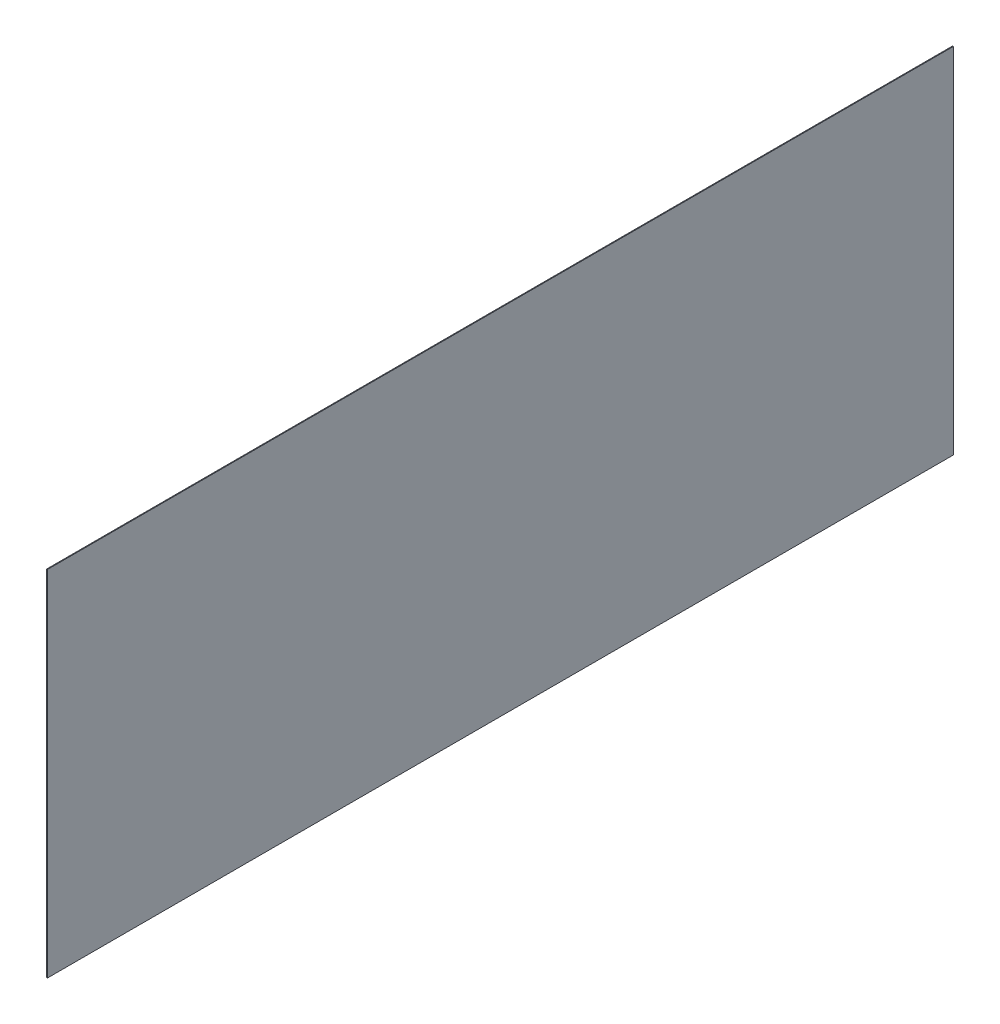
SolidWorks part; units mm, degrees
material "POLYURETHANE (11671)"
ref_plane "Front" through (0, 0, 0) normal (0, 0, 1) x (1, 0, 0)
ref_plane "Top" through (0, 0, 0) normal (0, 1, 0) x (1, 0, 0)
ref_plane "Right" through (0, 0, 0) normal (1, 0, 0) x (0, 0, -1)
sketch "Sketch1" plane through (0, 0, 0) normal (1, 0, 0) x (0, 0, -1)
  line L1 (-2876, 1123.5) -> (2876, 1123.5)
  line L2 (-2876, 1123.5) -> (-2876, -1123.5)
  line L3 (-2876, -1123.5) -> (2876, -1123.5)
  line L4 (2876, 1123.5) -> (2876, -1123.5)
  line L5 (-2876, 1123.5) -> (2876, -1123.5) construction
  line L6 (-2876, -1123.5) -> (2876, 1123.5) construction
  point P0 (0, 0)
  dimension "D1" = 5752
  dimension "D2" = 2247
extrude "Boss-Extrude1" add sketch "Sketch1" along normal blind 5
